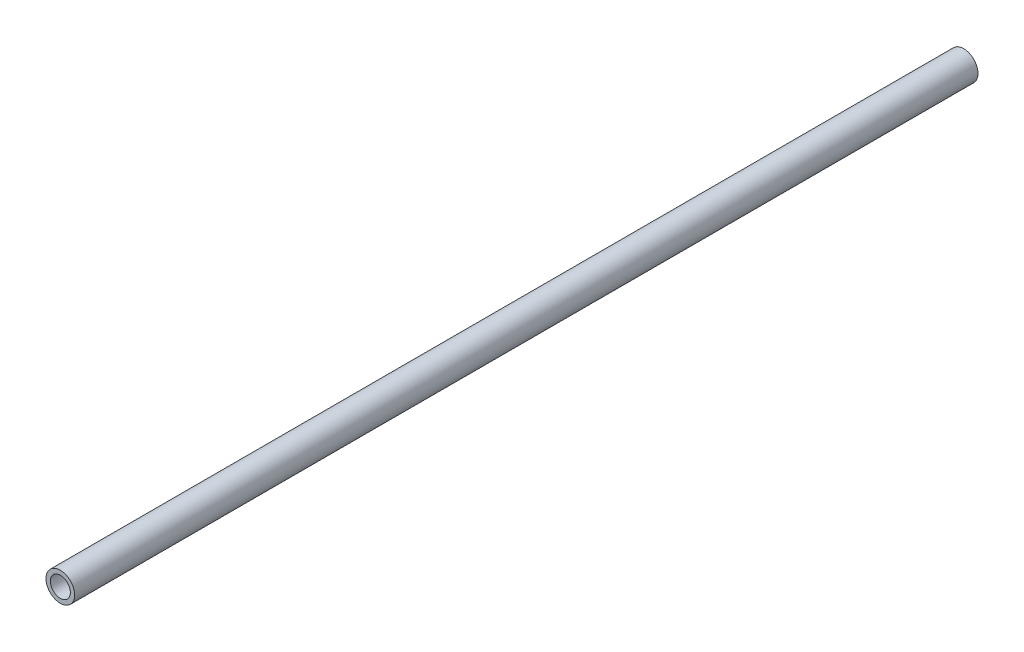
SolidWorks part; units mm, degrees
ref_plane "Front Plane" through (0, 0, 0) normal (1, 0, 0) x (0, 1, 0)
ref_plane "Top Plane" through (0, 0, 0) normal (0, 0, 1) x (0, 1, 0)
ref_plane "Right Plane" through (0, 0, 0) normal (0, 1, 0) x (-1, 0, 0)
sketch "Sketch1" plane through (0, 0, 0) normal (0, 0, 1) x (0, 1, 0)
  circle A0 centre (0, 0) radius 15.875
  circle A1 centre (0, 0) radius 11.1
  dimension "D1" = 31.75
  dimension "D2" = 22.2
extrude "Boss-Extrude1" add sketch "Sketch1" along normal blind 1000
equation "\"OD\"= 1.25in"
equation "\"ID\"= 22.2"
equation "\"D1@Sketch1\"=\"OD\""
equation "\"D2@Sketch1\"=\"ID\""
equation "\"L\" = 1000mm"
equation "\"D1@Boss-Extrude1\"=\"L\""
